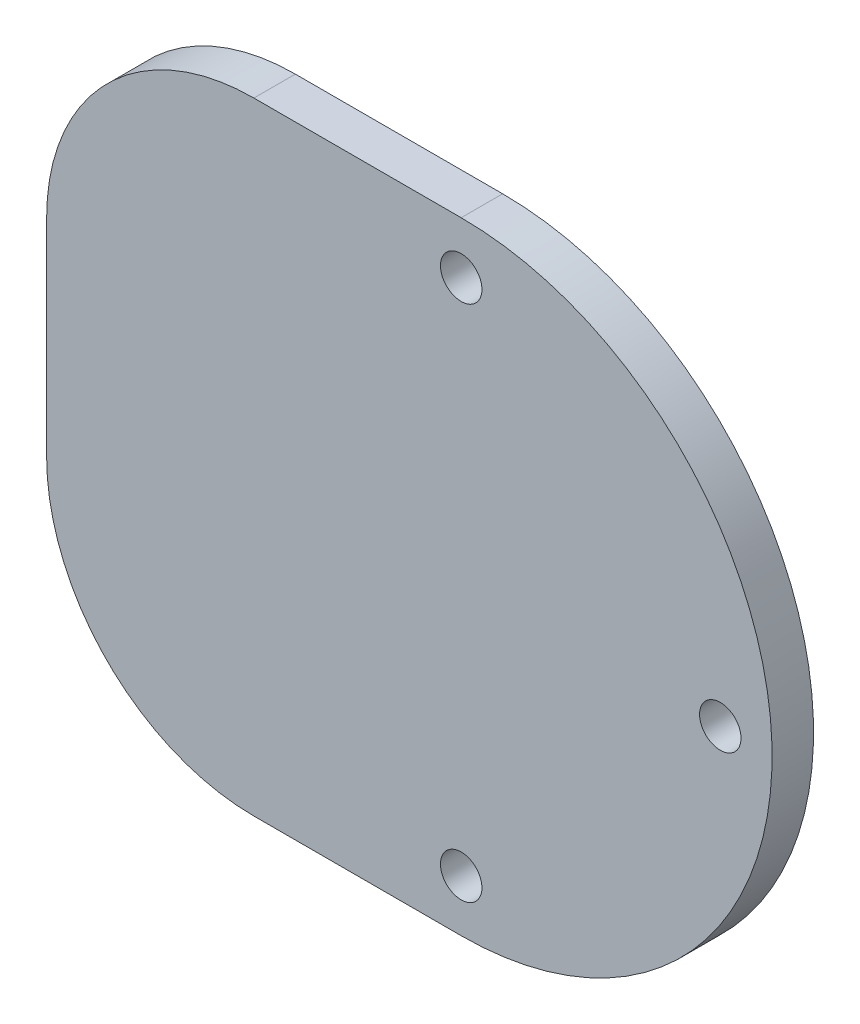
SolidWorks part; units mm, degrees
material "1060 Alloy"
ref_plane "Front" through (0, 0, 0) normal (0, 0, 1) x (1, 0, 0)
ref_plane "Top" through (0, 0, 0) normal (0, 1, 0) x (1, 0, 0)
ref_plane "Right" through (0, 0, 0) normal (1, 0, 0) x (0, 0, -1)
sketch "Sketch1" plane through (0, 0, 0) normal (0, 0, 1) x (1, 0, 0)
  line L0 (0, 75) -> (-100, 75)
  line L1 (-100, 75) -> (-100, -75)
  line L2 (-100, -75) -> (0, -75)
  arc A0 (0, -75) -> (0, 75) centre (0, 0) ccw
  dimension "D1" = 150
  dimension "D2" = 100
extrude "Boss-Extrude1" add sketch "Sketch1" along normal blind 10
sketch "Sketch2" plane through (0, 0, 10) normal (0, 0, 1) x (1, 0, 0)
  circle A0 centre (0, 0) radius 62.5
  circle A1 centre (0, 62.5) radius 5
  circle A2 centre (62.5, 0) radius 5
  circle A3 centre (0, -62.5) radius 5
  point P11 (0, 0)
  dimension "D1" = 125
  dimension "D2" = 10
  dimension "D3" = 3
extrude "Cut-Extrude1" cut sketch "Sketch2" against normal blind 10 contours A1 | A2 | A3
fillet "Fillet1" radius 50 2 edges at (-100, -75, 5) (-100, 75, 5)
